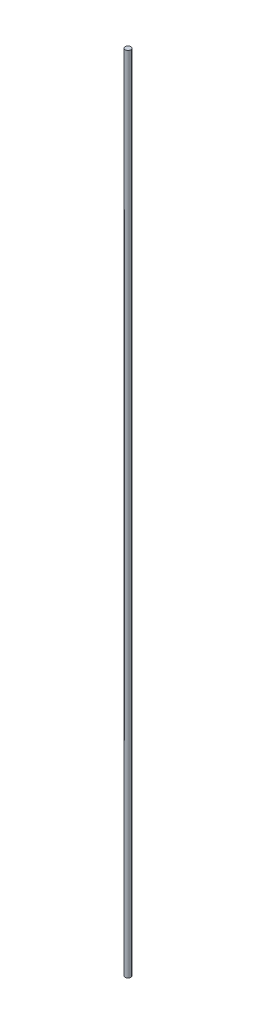
SolidWorks part; units mm, degrees
material "Nylon 101"
ref_plane "Alzado" through (0, 0, 0) normal (0, 0, 1) x (1, 0, 0)
ref_plane "Planta" through (0, 0, 0) normal (0, 1, 0) x (1, 0, 0)
ref_plane "Vista lateral" through (0, 0, 0) normal (1, 0, 0) x (0, 0, -1)
sketch "Sketch1" plane through (0, 0, 0) normal (0, 0, 1) x (1, 0, 0)
  line L0 (0, -1) -> (0.75, -1)
  line L1 (0.75, -1) -> (0.75, -220)
  line L2 (0.75, -220) -> (0, -220)
  line L3 (0, -220) -> (0, -1)
  line L4 (0, -224) -> (0, 3) construction
revolve "Varilla_carbono" add sketch "Sketch1" angle 360 about L4
